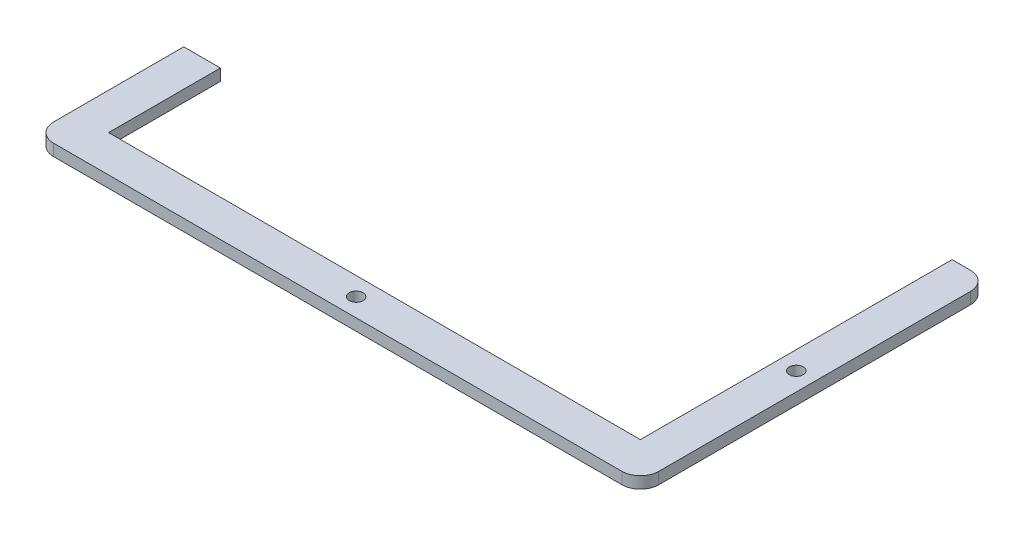
SolidWorks part; units mm, degrees
ref_plane "Front Plane" through (0, 0, 0) normal (0, 0, 1) x (1, 0, 0)
ref_plane "Top Plane" through (0, 0, 0) normal (0, 1, 0) x (1, 0, 0)
ref_plane "Right Plane" through (0, 0, 0) normal (1, 0, 0) x (0, 0, -1)
sketch "Sketch1" plane through (0, 0, 0) normal (0, 1, 0) x (1, 0, 0)
  line L0 (-165, 47.5) -> (0, 47.5) construction
  line L1 (-5, 0) -> (-160, 0)
  line L2 (0, 5) -> (0, 90)
  line L5 (-82.5, 95) -> (-82.5, 0) construction
  line L8 (-155, 10) -> (-10, 10)
  line L9 (-10, 85) -> (-10, 10)
  line L11 (-10, 85) -> (-10, 95)
  line L12 (-10, 95) -> (-5, 95)
  line L13 (-165, 40.5) -> (-155, 40.5)
  line L14 (-165, 40.5) -> (-165, 5)
  line L15 (-155, 40.5) -> (-155, 10)
  line L16 (-155, 10) -> (-155.5312, 10.2787)
  arc A0 (-160, 0) -> (-165, 5) centre (-160, 5) cw
  arc A1 (-5, 0) -> (0, 5) centre (-5, 5) ccw
  arc A2 (0, 90) -> (-5, 95) centre (-5, 90) ccw
  circle A5 centre (-5, 47.5) radius 1.875
  circle A7 centre (-82.5, 5) radius 1.875
  point P9 (0, 0)
  dimension "D3" = 5
  dimension "D4" = 10
  dimension "D6" = 3.75
  dimension "D14" = 95
  dimension "D15" = 3.75
  dimension "D2" = 165
  dimension "D7" = 5
  dimension "D10" = 10
  dimension "D11" = 10
  dimension "D12" = 5
extrude "Boss-Extrude1" add sketch "Sketch1" along normal blind 3.175
